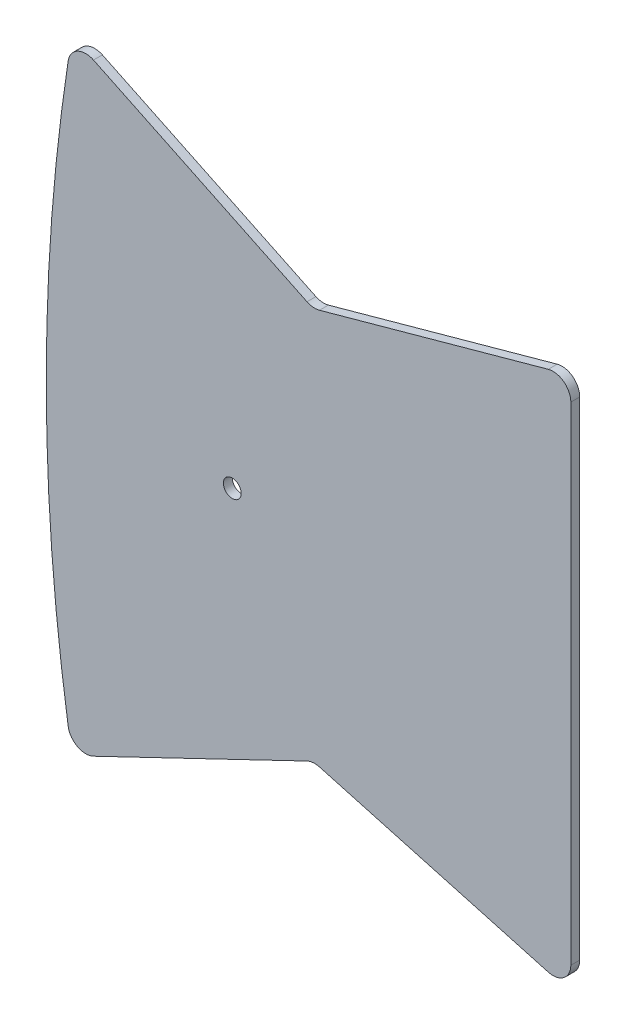
SolidWorks part; units mm, degrees
ref_plane "Front Plane" through (0, 0, 0) normal (0, 0, 1) x (1, 0, 0)
ref_plane "Top Plane" through (0, 0, 0) normal (0, 1, 0) x (1, 0, 0)
ref_plane "Right Plane" through (0, 0, 0) normal (1, 0, 0) x (0, 0, -1)
sketch "Sketch1" plane through (0, 0, 0) normal (0, 0, 1) x (1, 0, 0)
  line L0 (-177.8, 111.125) -> (-91.8766, 69.85)
  line L1 (-91.8766, 69.85) -> (0, 95.25)
  line L2 (0, 95.25) -> (0, -95.25)
  line L3 (0, -95.25) -> (-91.8766, -69.85)
  line L4 (-91.8766, -69.85) -> (-177.8, -111.125)
  arc A0 (-177.8, 111.125) -> (-177.8, -111.125) centre (492.5011, 0) ccw
  circle A2 centre (-120.65, 0) radius 3.175
  point P3 (0, 0)
  point P8 (-186.9489, 0)
  point P10 (0, 0)
  dimension "D1" = 679.45
  dimension "D4" = 177.8
  dimension "D6" = 6.35
  dimension "D2" = 190.5
  dimension "D3" = 25.4
  dimension "D5" = 15.875
  dimension "D7" = 120.65
extrude "Boss-Extrude1" add sketch "Sketch1" along normal blind 3.175
fillet "Fillet1" radius 6.35 6 edges at (-91.8766, 69.85, 1.5875) (0, 95.25, 1.5875) (0, -95.25, 1.5875) (-91.8766, -69.85, 1.5875) (-177.8, -111.125, 1.5875) (-177.8, 111.125, 1.5875)
